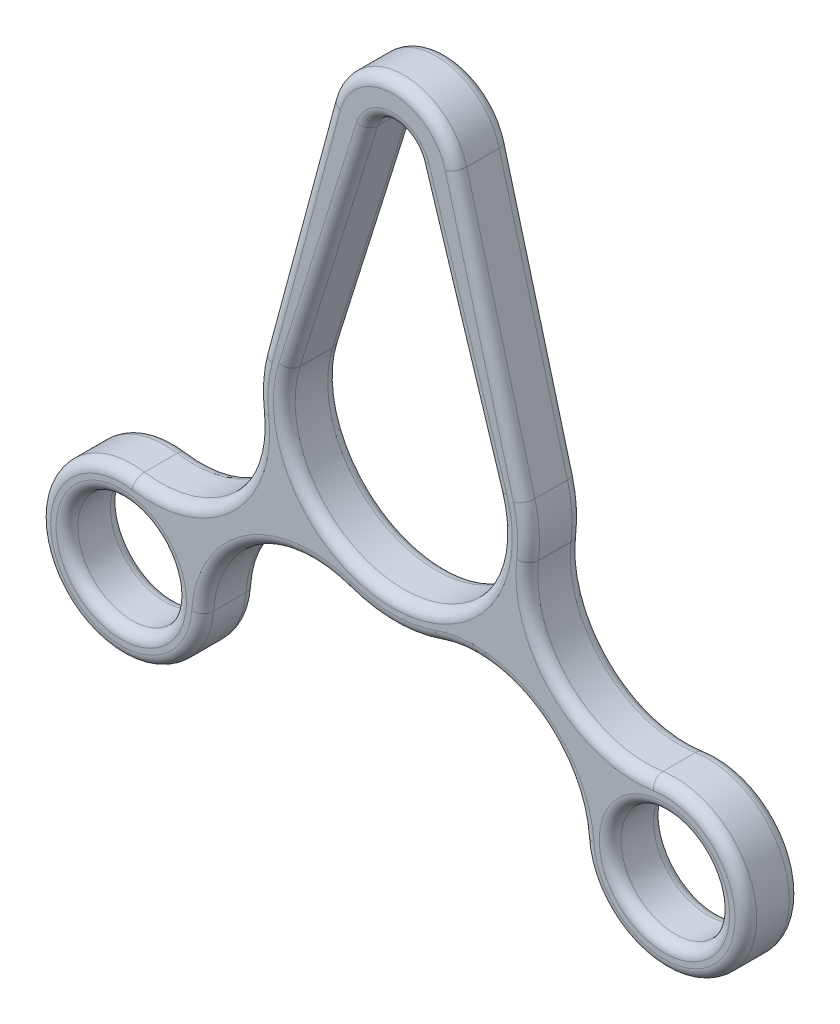
SolidWorks part; units mm, degrees
ref_plane "Front Plane" through (0, 0, 0) normal (0, 0, 1) x (1, 0, 0)
ref_plane "Top Plane" through (0, 0, 0) normal (0, 1, 0) x (1, 0, 0)
ref_plane "Right Plane" through (0, 0, 0) normal (1, 0, 0) x (0, 0, -1)
sketch "Sketch1" plane through (0, 0, 0) normal (0, 0, 1) x (1, 0, 0)
  line L0 (0, 0) -> (0, 50) construction
  line L1 (-11.5873, 53.12) -> (-24.1402, 6.5)
  line L2 (11.5873, 53.12) -> (24.1402, 6.5)
  line L3 (-4.7697, 51.5) -> (-19.0788, 6)
  line L4 (4.7697, 51.5) -> (19.0788, 6)
  arc A0 (-19.0788, 6) -> (19.0788, 6) centre (0, 0) ccw
  arc A1 (-24.1402, 6.5) -> (-24.8188, -3.0042) centre (0, 0) ccw
  arc A2 (4.7697, 51.5) -> (-4.7697, 51.5) centre (0, 50) ccw
  arc A4 (35.0352, -41.0274) -> (47.7174, -25.1747) centre (50, -40) ccw
  circle A5 centre (50, -40) radius 10
  circle A6 centre (-50, -40) radius 10
  arc A7 (-35.0352, -41.0274) -> (-47.7174, -25.1747) centre (-50, -40) cw
  arc A8 (24.8188, -3.0042) -> (47.7174, -25.1747) centre (44.6739, -5.4076) ccw
  arc A9 (8.379, -23.554) -> (35.0352, -41.0274) centre (15.0822, -42.3973) cw
  arc A10 (-8.379, -23.554) -> (-35.0352, -41.0274) centre (-15.0822, -42.3973) ccw
  arc A11 (-24.8188, -3.0042) -> (-47.7174, -25.1747) centre (-44.6739, -5.4076) cw
  arc A12 (11.5873, 53.12) -> (-11.5873, 53.12) centre (0, 50) ccw
  arc A13 (24.8188, -3.0042) -> (24.1402, 6.5) centre (0, 0) ccw
  arc A14 (-8.379, -23.554) -> (8.379, -23.554) centre (0, 0) ccw
  dimension "D1" = 40
  dimension "D2" = 50
  dimension "D3" = 10
  dimension "D4" = 12
  dimension "D6" = 30
  dimension "D7" = 20
  dimension "D10" = 20
  dimension "D11" = 20
  dimension "D5" = 50
  dimension "D8" = 50
  dimension "D9" = 40
extrude "Boss-Extrude1" add sketch "Sketch1" along normal mid plane 10
fillet "Fillet1" radius 2 36 edges at (17.8638, 29.81, 5) (24.9365, 1.7805, 5) (30.762, -19.7763, 5) (61.713, -49.3704, 5) (26.0466, -25.6706, 5) (0, -25, 5) (-26.0466, -25.6706, 5) (-61.713, -49.3704, 5) (-30.762, -19.7763, 5) (-24.9365, 1.7805, 5) (-17.8638, 29.81, 5) (0, 62, 5) (17.8638, 29.81, -5) (24.9365, 1.7805, -5) (30.762, -19.7763, -5) (61.713, -49.3704, -5) (26.0466, -25.6706, -5) (0, -25, -5) (-26.0466, -25.6706, -5) (-61.713, -49.3704, -5) (-30.762, -19.7763, -5) (-24.9365, 1.7805, -5) (-17.8638, 29.81, -5) (0, 62, -5) (60, -40, 5) (60, -40, -5) (-60, -40, 5) (-60, -40, -5) (11.9242, 28.75, 5) (0, -20, 5) (-11.9242, 28.75, 5) (0, 55, 5) (11.9242, 28.75, -5) (0, -20, -5) (-11.9242, 28.75, -5) (0, 55, -5)
